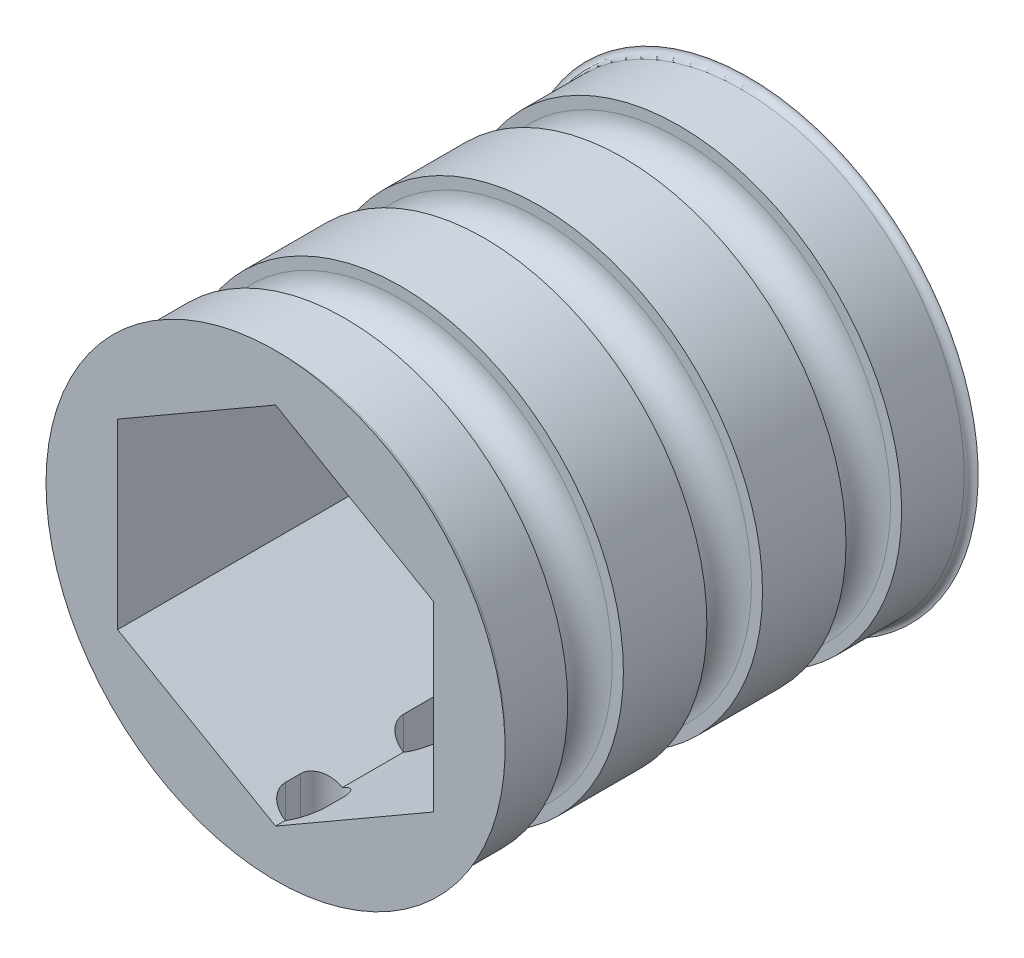
SolidWorks part; units mm, degrees
ref_plane "Plan de face" through (0, 0, 0) normal (0, 0, 1) x (1, 0, 0)
ref_plane "Plan de dessus" through (0, 0, 0) normal (0, 1, 0) x (1, 0, 0)
ref_plane "Plan de droite" through (0, 0, 0) normal (1, 0, 0) x (0, 0, -1)
sketch "Esquisse1" plane through (0, 0, 0) normal (0, 0, 1) x (1, 0, 0)
  circle A0 centre (0, 0) radius 3.25
  circle A1 centre (0, 0) radius 17
  dimension "D1" = 34
  dimension "D2" = 6.5
extrude "Boss.-Extru.1" add sketch "Esquisse1" along normal blind 34
sketch "Esquisse9" plane through (0, 0, 34) normal (0, 0, 1) x (1, 0, 0)
  line L0 (0, 0) -> (0, 26.2117) construction
  line L1 (11.35, -6.5529) -> (11.35, 6.5529)
  line L2 (11.35, 6.5529) -> (0, 13.1059)
  line L3 (0, 13.1059) -> (-11.35, 6.5529)
  line L4 (-11.35, 6.5529) -> (-11.35, -6.5529)
  line L5 (-11.35, -6.5529) -> (0, -13.1059)
  line L6 (0, -13.1059) -> (11.35, -6.5529)
  circle A0 centre (0, 0) radius 11.35 construction
  dimension "D1" = 22.7
extrude "Enlèv. mat.-Extru.9" cut sketch "Esquisse9" against normal offset from surface (18 mm away) 16 up to face at (17, 0, 0)
sketch "Esquisse11" plane through (0, 0, 0) normal (0, 0, -1) x (-1, 0, 0)
  circle A1 centre (-6.9282, 4) radius 2.1
  circle A2 centre (6.9282, 4) radius 2.1
  circle A3 centre (0, -8) radius 2.1
  circle A4 centre (0, 0) radius 8 construction
  dimension "D3" = 4.2
  dimension "D4" = 16
extrude "Enlèv. mat.-Extru.10" cut sketch "Esquisse11" against normal through all
sketch "Esquisse12" plane through (0, 0, 0) normal (0, 0, -1) x (-1, 0, 0)
  circle A0 centre (-6.9282, 4) radius 4.25
  circle A1 centre (6.9282, 4) radius 4.25
  circle A2 centre (0, -8) radius 4.25
  dimension "D1" = 8.5
extrude "Enlèv. mat.-Extru.11" cut sketch "Esquisse12" against normal blind 4
sketch "Esquisse13" plane through (0, 0, 0) normal (0, 1, 0) x (1, 0, 0)
  line L0 (-17, -34) -> (-16.5, -34)
  line L1 (-17, -34) -> (17, -34) construction
  line L2 (-16, -33.5) -> (-16, -29)
  line L3 (0, 0) -> (0, -49.3031) construction
  line L4 (-16, -25) -> (-16, -19)
  line L5 (-17, 0) -> (-17, -34) construction
  line L6 (-16, -15) -> (-16, -9)
  line L7 (-17, -17) -> (17, -17) construction
  line L8 (-16, -5) -> (-16, -0.5)
  line L9 (-17, 0) -> (17, 0) construction
  line L10 (-16.5, 0) -> (-17, 0)
  line L11 (-17, 0) -> (-17, -34)
  line L12 (17, -34) -> (17, 0) construction
  line L13 (-15.7, -34) -> (-15.7, 0) construction
  line L14 (-16, -5) -> (-15.2, -5)
  line L15 (-15.2, -9) -> (-16, -9)
  line L16 (-16, -15) -> (-15.2, -15)
  line L17 (-15.2, -19) -> (-16, -19)
  line L18 (-16, -25) -> (-15.2, -25)
  line L19 (-15.2, -29) -> (-16, -29)
  arc A0 (-15.2, -5) -> (-15.2, -9) centre (-15.2, -7) cw
  arc A1 (-15.2, -15) -> (-15.2, -19) centre (-15.2, -17) cw
  arc A2 (-15.2, -25) -> (-15.2, -29) centre (-15.2, -27) cw
  arc A3 (-16.5, -34) -> (-16, -33.5) centre (-16.5, -33.5) ccw
  arc A4 (-16, -0.5) -> (-16.5, 0) centre (-16.5, -0.5) ccw
  point P20 (-16, -34)
  point P23 (-16, 0)
  dimension "D15" = 0.5
  dimension "D2" = 2
  dimension "D3" = 0.8
  dimension "D4" = 10
  dimension "D14" = 1
revolve "Enlèvement de matière-Révolution1" cut sketch "Esquisse13" angle 360 about L3
sketch "Esquisse14" plane through (0, 0, 0) normal (0, 0, -1) x (-1, 0, 0)
  circle A0 centre (0, 0) radius 13.1059
extrude "Enlèv. mat.-Extru.12" cut sketch "Esquisse14" against normal offset from surface (12 mm away) 4 up to face at (-4.8282, 4, 16)
sketch "Esquisse15" plane through (0, 0, 0) normal (0, 1, 0) x (1, 0, 0)
  line L0 (0, -20.7) -> (0, -23.3) construction
  line L1 (1.5, -20.7) -> (1.5, -23.3)
  line L2 (-1.5, -20.7) -> (-1.5, -23.3)
  line L3 (-16.5, -34) -> (16.5, -34) construction
  line L7 (0, -30.7) -> (0, -31.8) construction
  line L8 (1.5, -30.7) -> (1.5, -31.8)
  line L9 (-1.5, -30.7) -> (-1.5, -31.8)
  line L10 (0, -6.51) -> (0, -9.479) construction
  line L11 (1.5, -6.51) -> (1.5, -9.479) construction
  line L12 (-1.5, -6.51) -> (-1.5, -9.479) construction
  line L13 (-3.5804, -29.2) -> (3.3426, -29.2) construction
  line L15 (15.2, -29) -> (-15.2, -29) construction
  line L17 (-3.5804, -33.3) -> (3.3426, -33.3) construction
  line L18 (-16, -33.5) -> (16, -33.5) construction
  line L19 (-3.5804, -24.8) -> (3.3426, -24.8) construction
  line L20 (3.3426, -19.2) -> (-3.5804, -19.2) construction
  line L21 (-15.2, -25) -> (15.2, -25) construction
  line L22 (16, -19) -> (-16, -19) construction
  arc A0 (1.5, -20.7) -> (-1.5, -20.7) centre (0, -20.7) ccw
  arc A1 (-1.5, -23.3) -> (1.5, -23.3) centre (0, -23.3) ccw
  arc A2 (1.5, -30.7) -> (-1.5, -30.7) centre (0, -30.7) ccw
  arc A3 (-1.5, -31.8) -> (1.5, -31.8) centre (0, -31.8) ccw
  arc A4 (1.5, -6.51) -> (-1.5, -6.51) centre (0, -6.51) ccw construction
  arc A5 (-1.5, -9.479) -> (1.5, -9.479) centre (0, -9.479) ccw construction
  point P3 (0, -22)
  point P8 (0, -31.25)
  point P19 (0, -7.9945)
  dimension "D3" = 1.5
  dimension "D2" = 0.2
  dimension "D5" = 0.2
  dimension "D1" = 0.2
  dimension "D4" = 12
  dimension "D6" = 0.2
extrude "Enlèv. mat.-Extru.13" cut sketch "Esquisse15" against normal through all
